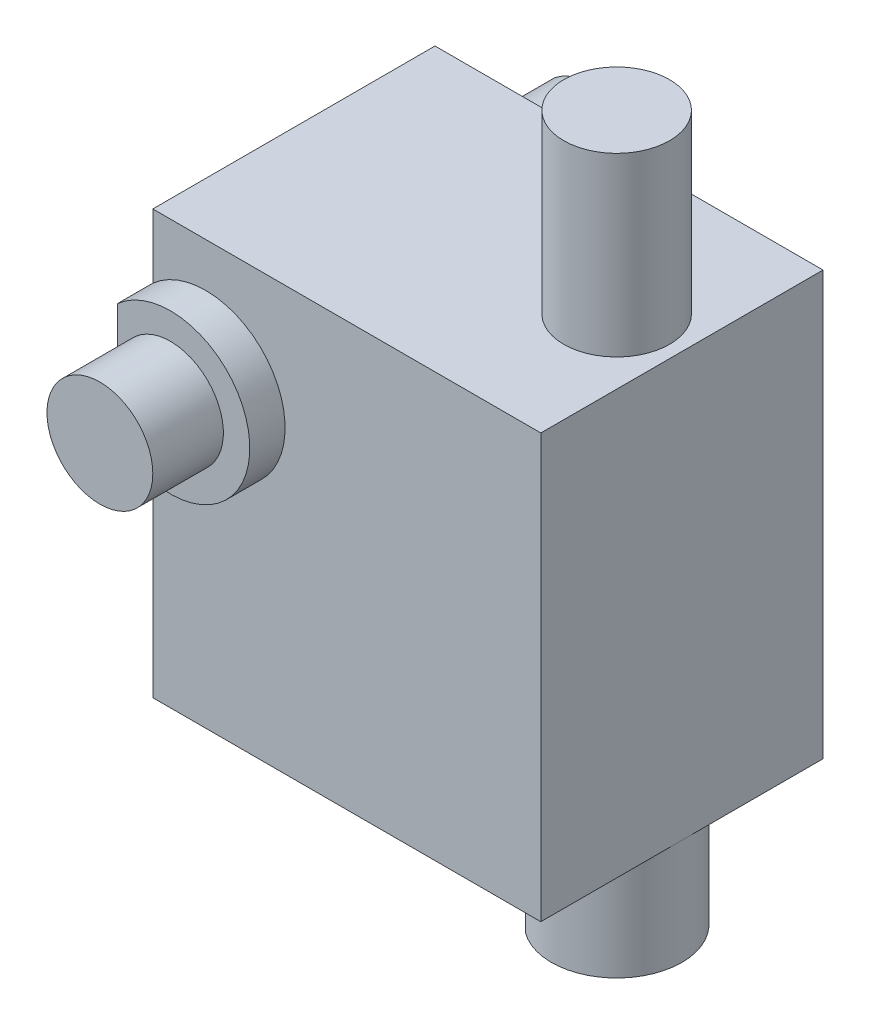
SolidWorks part; units mm, degrees
ref_plane "Front Plane" through (0, 0, 0) normal (0, 0, 1) x (1, 0, 0)
ref_plane "Top Plane" through (0, 0, 0) normal (0, 1, 0) x (1, 0, 0)
ref_plane "Right Plane" through (0, 0, 0) normal (1, 0, 0) x (0, 0, -1)
sketch "Sketch1" plane through (0, 0, 0) normal (0, 1, 0) x (1, 0, 0)
  line L0 (-1.1, 1.4874) -> (-1.1, -1.4874)
  arc A0 (-1.1, -1.4874) -> (-1.1, 1.4874) centre (0, 0) ccw
  arc A1 (-1.1, 1.4874) -> (-1.1, -1.4874) centre (0, 0) ccw construction
  dimension "D1" = 3.7
  dimension "D2" = 1.1
extrude "Boss-Extrude1" add sketch "Sketch1" along normal blind 3
sketch "Sketch2" plane through (0, 3, 0) normal (0, 1, 0) x (1, 0, 0)
  line L1 (1.85, -4) -> (-9.15, -4)
  line L2 (1.85, -4) -> (1.85, 4)
  line L3 (1.85, 4) -> (-9.15, 4)
  line L4 (-9.15, -4) -> (-9.15, 4)
  arc A0 (-1.1, -1.4874) -> (-1.1, 1.4874) centre (0, 0) ccw construction
  point P0 (0, 0)
  dimension "D1" = 4
  dimension "D2" = 4
  dimension "D3" = 11
extrude "Boss-Extrude2" add sketch "Sketch2" along normal blind 12
sketch "Sketch4" plane through (0, 15, 0) normal (0, 1, 0) x (1, 0, 0)
  circle A0 centre (0, 0) radius 1.5
  dimension "D1" = 3
extrude "Boss-Extrude4" add sketch "Sketch4" along normal blind 5
sketch "Sketch5" plane through (0, 0, 0) normal (0, 0, 1) x (1, 0, 0)
  line L0 (-9.15, 13.1771) -> (-9.15, 9.8229)
  line L1 (-9.15, 15) -> (-9.15, 3) construction
  line L2 (-9.15, 3) -> (1.85, 3) construction
  arc A0 (-9.15, 9.8229) -> (-9.15, 13.1771) centre (-7.65, 11.5) ccw
  arc A1 (-9.15, 13.1771) -> (-9.15, 9.8229) centre (-7.65, 11.5) ccw construction
  dimension "D1" = 4.5
  dimension "D2" = 8.5
  dimension "D3" = 1.5
extrude "Boss-Extrude5" add sketch "Sketch5" along normal mid plane 10
sketch "Sketch3" plane through (0, 0, 5) normal (0, 0, 1) x (1, 0, 0)
  line L0 (-9.15, 15) -> (-9.15, 13.1771) construction
  line L1 (-9.15, 3) -> (1.85, 3) construction
  circle A0 centre (-7.65, 11.5) radius 1.5
  dimension "D1" = 3
  dimension "D2" = 8.5
extrude "Boss-Extrude3" add sketch "Sketch3" along normal blind 2
sketch "Sketch6" plane through (0, 0, -5) normal (0, 0, -1) x (-1, 0, 0)
  line L0 (8.75, 10.0752) -> (8.75, 12.9248)
  arc A0 (8.75, 12.9248) -> (8.75, 10.0752) centre (7.65, 11.5) ccw
  arc A1 (8.75, 10.0752) -> (8.75, 12.9248) centre (7.65, 11.5) ccw construction
  dimension "D1" = 3.6
  dimension "D2" = 1.1
extrude "Boss-Extrude6" add sketch "Sketch6" along normal blind 2
